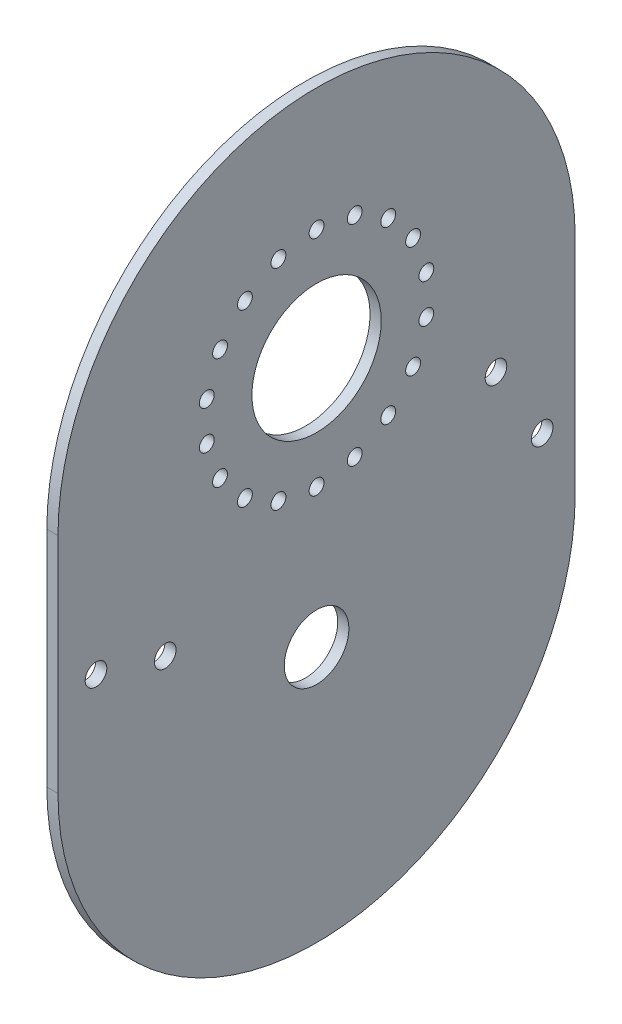
SolidWorks part; units mm, degrees
ref_plane "Front Plane" through (0, 0, 0) normal (0, 0, 1) x (1, 0, 0)
ref_plane "Top Plane" through (0, 0, 0) normal (0, 1, 0) x (1, 0, 0)
ref_plane "Right Plane" through (0, 0, 0) normal (1, 0, 0) x (0, 0, -1)
sketch "Sketch1" plane through (0, 0, 0) normal (1, 0, 0) x (0, 0, -1)
  line L4 (0, 50.1) -> (0, -50.1) construction
  line L5 (116, 50.1) -> (116, -50.1)
  line L6 (-116, 50.1) -> (-116, -50.1)
  line L10 (0, -50.1) -> (0, -51.2443)
  line L13 (0, -36.7443) -> (0, -50.1)
  circle A0 centre (0, 61.0772) radius 29
  circle A1 centre (0, -51.2443) radius 14.5
  circle A3 centre (80.4727, 15.3809) radius 4.85
  arc A4 (116, 50.1) -> (-116, 50.1) centre (0, 50.1) ccw
  arc A5 (-116, -50.1) -> (116, -50.1) centre (0, -50.1) ccw
  circle A6 centre (101.2105, -18.7156) radius 4.85
  circle A7 centre (-67.8988, -20.7242) radius 4.85
  circle A8 centre (-98.9458, -12.3675) radius 4.85
  point P11 (0, 0)
  point P16 (0, -166.1)
  point P17 (0, 166.1)
  dimension "D6" = 58
  dimension "D8" = 29
  dimension "D9" = 9.7
  dimension "D14" = 9.7
  dimension "D15" = 9.7
  dimension "D16" = 9.7
  dimension "D1" = 112.3215
  dimension "D2" = 128.8815
  dimension "D4" = 104.4738
  dimension "D5" = 106.3095
  dimension "D10" = 232
  dimension "D11" = 332.2
  dimension "D13" = 32.152
extrude "Boss-Extrude1" add sketch "Sketch1" along normal blind 5
scale "Scale1" scale about centroid uniform scaling yes scale factor 1.5
sketch "Sketch2" plane through (6.25, 0, 0) normal (1, 0, 0) x (0, 0, -1)
  circle A0 centre (0.0089, 92.6237) radius 75 construction
  circle A1 centre (0.0089, 167.6237) radius 5
  circle A2 centre (25.6604, 163.1007) radius 5
  circle A3 centre (48.2179, 150.0771) radius 5
  circle A4 centre (64.9608, 130.1237) radius 5
  circle A5 centre (73.8694, 105.6474) radius 5
  circle A6 centre (73.8694, 79.6001) radius 5
  circle A7 centre (64.9608, 55.1237) radius 5
  circle A8 centre (48.2179, 35.1704) radius 5
  circle A9 centre (25.6604, 22.1468) radius 5
  circle A10 centre (0.0089, 17.6237) radius 5
  circle A11 centre (-25.6427, 22.1468) radius 5
  circle A12 centre (-48.2002, 35.1704) radius 5
  circle A13 centre (-64.9431, 55.1237) radius 5
  circle A14 centre (-73.8517, 79.6001) radius 5
  circle A15 centre (-73.8517, 105.6474) radius 5
  circle A16 centre (-64.9431, 130.1237) radius 5
  circle A17 centre (-48.2002, 150.0771) radius 5
  circle A18 centre (-25.6427, 163.1007) radius 5
  point P41 (0.0089, 92.6237)
  dimension "D1" = 150
  dimension "D2" = 10
  dimension "D3" = 18
extrude "Cut-Extrude1" cut sketch "Sketch2" against normal blind 10
